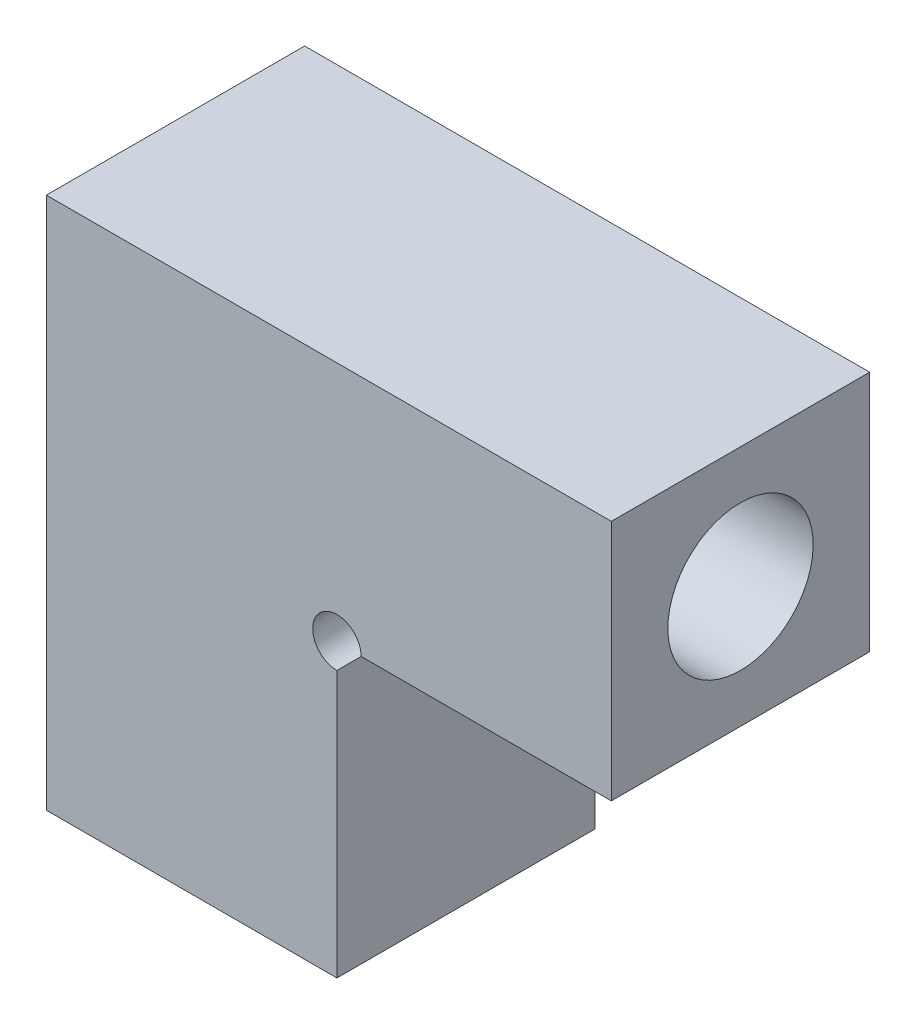
SolidWorks part; units mm, degrees
material "AISI 1045 Aço, trefilado"
ref_plane "Plano frontal" through (0, 0, 0) normal (0, 0, 1) x (1, 0, 0)
ref_plane "Plano superior" through (0, 0, 0) normal (0, 1, 0) x (1, 0, 0)
ref_plane "Plano direito" through (0, 0, 0) normal (1, 0, 0) x (0, 0, -1)
sketch "Esboço2" plane through (0, 0, 0) normal (0, 0, 1) x (1, 0, 0)
  line L0 (0, 0) -> (0, 33)
  line L1 (0, 33) -> (35, 33)
  line L2 (35, 33) -> (35, 18)
  line L3 (35, 18) -> (18, 18)
  line L4 (18, 18) -> (18, 0)
  line L5 (18, 0) -> (0, 0)
  circle A0 centre (18, 18) radius 1.5
  point P3 (26.5, 18)
  dimension "D5" = 3
  dimension "D1" = 18
  dimension "D2" = 35
  dimension "D3" = 33
  dimension "D4" = 18
extrude "Ressalto-extrusão1" add sketch "Esboço2" along normal blind 16 contours A0 L3 L2 L1 L0 L5 L4
sketch "Esboço5" plane through (35, 0, 0) normal (1, 0, 0) x (0, 0, -1)
  line L0 (-16, 18) -> (0, 18) construction
  circle A0 centre (-8, 25.5) radius 4.5
  dimension "D1" = 9
  dimension "D2" = 7.5
extrude "Corte-extrusão1" cut sketch "Esboço5" against normal through all
